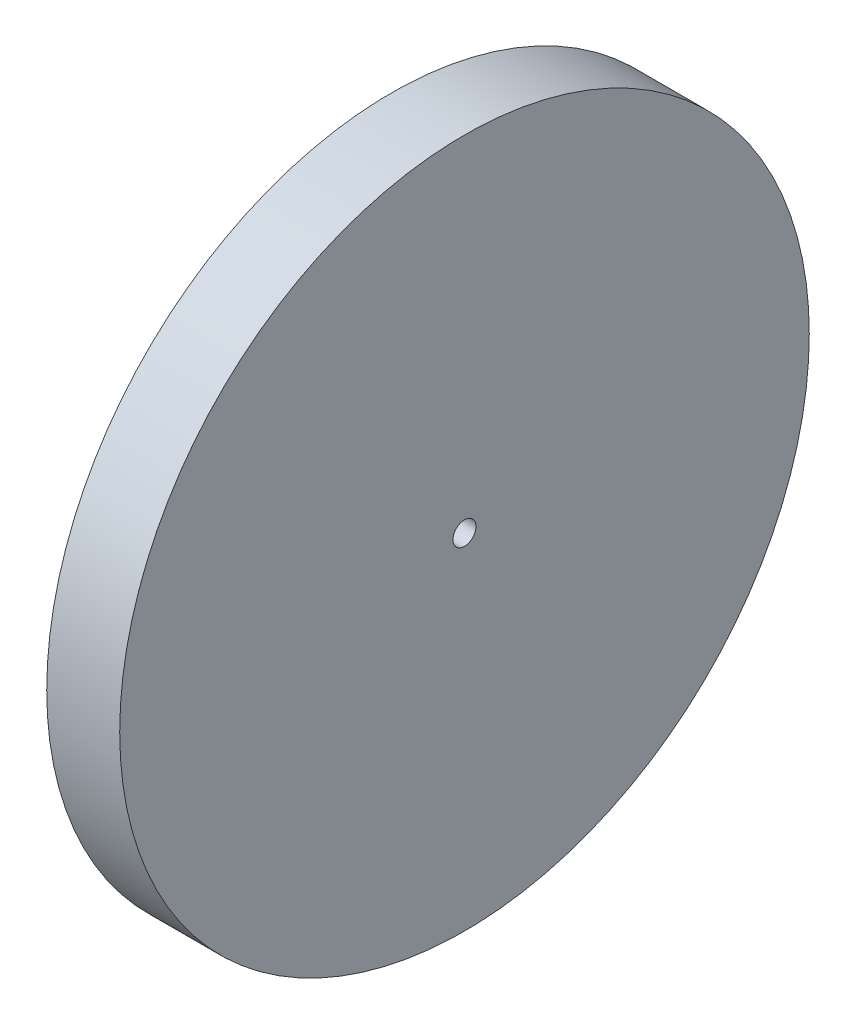
SolidWorks part; units mm, degrees
ref_plane "Front Plane" through (0, 0, 0) normal (0, 0, 1) x (1, 0, 0)
ref_plane "Top Plane" through (0, 0, 0) normal (0, 1, 0) x (1, 0, 0)
ref_plane "Right Plane" through (0, 0, 0) normal (1, 0, 0) x (0, 0, -1)
sketch "Sketch1" plane through (0, 0, 0) normal (1, 0, 0) x (0, 0, -1)
  circle A0 centre (0, 0) radius 30
  circle A1 centre (0, 0) radius 1
  dimension "D1" = 2
  dimension "D2" = 60
extrude "Boss-Extrude1" add sketch "Sketch1" along normal blind 6.35
